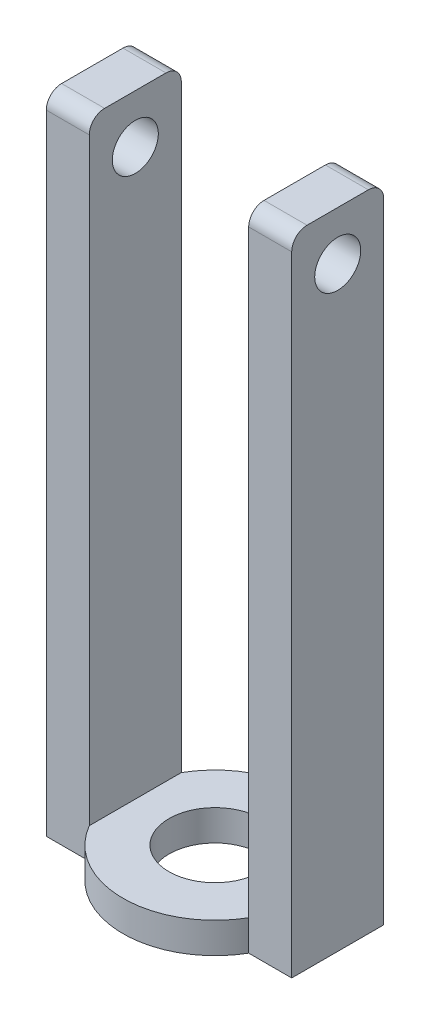
SolidWorks part; units mm, degrees
ref_plane "Front Plane" through (0, 0, 0) normal (0, 0, 1) x (1, 0, 0)
ref_plane "Top Plane" through (0, 0, 0) normal (0, 1, 0) x (1, 0, 0)
ref_plane "Right Plane" through (0, 0, 0) normal (1, 0, 0) x (0, 0, -1)
sketch "Sketch1" plane through (0, 0, 0) normal (0, 1, 0) x (1, 0, 0)
  line L1 (-400, 150) -> (400, 150)
  line L2 (-400, 150) -> (-400, -150)
  line L3 (-400, -150) -> (400, -150)
  line L4 (400, 150) -> (400, -150)
  circle A0 centre (0, 0) radius 300
  dimension "D1" = 400
  dimension "D5" = 600
  dimension "D2" = 400
  dimension "D3" = 150
  dimension "D4" = 150
extrude "Boss-Extrude1" add sketch "Sketch1" along normal blind 100 contours L1 A0 | L3 A0 L1 | L3 A0 | A0 L1 L2 L3 | A0 L3 L4 L1
sketch "Sketch2" plane through (0, 100, 0) normal (0, 1, 0) x (1, 0, 0)
  line L1 (-400, 150) -> (-259.8076, 150)
  line L2 (-400, 150) -> (-400, -150)
  line L3 (-400, -150) -> (-259.8076, -150)
  line L4 (-259.8076, 150) -> (-259.8076, -150)
  line L5 (259.8076, 150) -> (400, 150)
  line L6 (259.8076, 150) -> (259.8076, -150)
  line L7 (259.8076, -150) -> (400, -150)
  line L8 (400, 150) -> (400, -150)
extrude "Boss-Extrude2" add sketch "Sketch2" along normal blind 2000 contours L2 L1 L4 L3 | L6 L5 L8 L7
sketch "Sketch3" plane through (0, 100, 0) normal (0, 1, 0) x (1, 0, 0)
  circle A0 centre (0, 0) radius 150
extrude "Cut-Extrude1" cut sketch "Sketch3" against normal blind 100
fillet "Fillet1" radius 50 4 edges at (-329.9038, 2100, 150) (-329.9038, 2100, -150) (329.9038, 2100, 150) (329.9038, 2100, -150)
sketch "Sketch4" plane through (-400, 0, 0) normal (-1, 0, 0) x (0, 0, 1)
  line L0 (-100, 2100) -> (100, 2100) construction
  circle A0 centre (0, 1941.16) radius 75
  dimension "D1" = 158.84
extrude "Cut-Extrude2" cut sketch "Sketch4" against normal up to vertex
